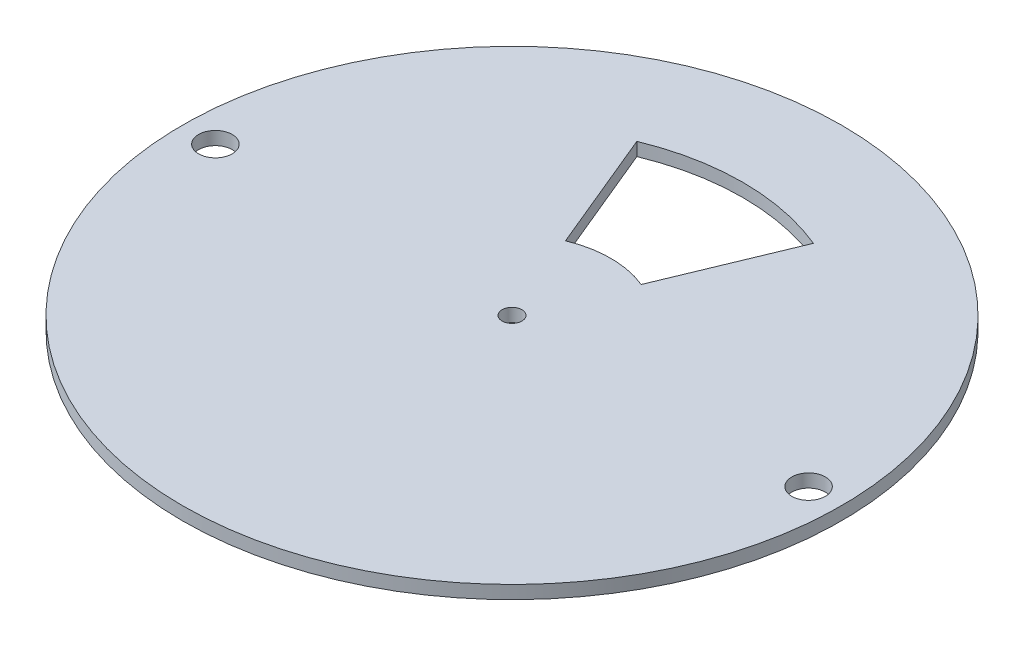
SolidWorks part; units mm, degrees
ref_plane "Front Plane" through (0, 0, 0) normal (0, 0, 1) x (1, 0, 0)
ref_plane "Top Plane" through (0, 0, 0) normal (0, 1, 0) x (1, 0, 0)
ref_plane "Right Plane" through (0, 0, 0) normal (1, 0, 0) x (0, 0, -1)
sketch "Sketch2" plane through (0, 0, 0) normal (0, 1, 0) x (1, 0, 0)
  circle A0 centre (0, 0) radius 50
  dimension "D1" = 100
extrude "Boss-Extrude1" add sketch "Sketch2" along normal blind 2
sketch "Sketch3" plane through (0, 2, 0) normal (0, 1, 0) x (1, 0, 0)
  line L0 (0, 0) -> (-13.3939, 32.3358) construction
  line L1 (13.3939, 32.3358) -> (0, 0) construction
  line L2 (-13.3939, 32.3358) -> (13.3939, 32.3358) construction
  line L3 (-5.7403, 13.8582) -> (-13.3939, 32.3358)
  line L4 (13.3939, 32.3358) -> (5.7403, 13.8582)
  arc A0 (-13.3939, 32.3358) -> (13.3939, 32.3358) centre (0, 0) cw
  arc A1 (-5.7403, 13.8582) -> (5.7403, 13.8582) centre (0, 0) cw
  point P4 (0, 32.3358)
  dimension "D2" = 35
  dimension "D3" = 15
  dimension "D1" = 45
extrude "Cut-Extrude1" cut sketch "Sketch3" against normal up to next contours L4 A1 L3 A0
sketch "Sketch4" plane through (0, 2, 0) normal (0, 1, 0) x (1, 0, 0)
  circle A0 centre (45, 0) radius 2.55
  dimension "D1" = 5.1
  dimension "D2" = 45
extrude "Cut-Extrude2" cut sketch "Sketch4" against normal through all contours A0
pattern_circular "CirPattern1" count 2 over 360 about axis through (0, 0, 0) along (0, 1, 0) of "Cut-Extrude2"
sketch "Sketch5" plane through (0, 2, 0) normal (0, 1, 0) x (1, 0, 0)
  circle A0 centre (0, 0) radius 1.5
  dimension "D1" = 3
extrude "Cut-Extrude3" cut sketch "Sketch5" against normal through all
